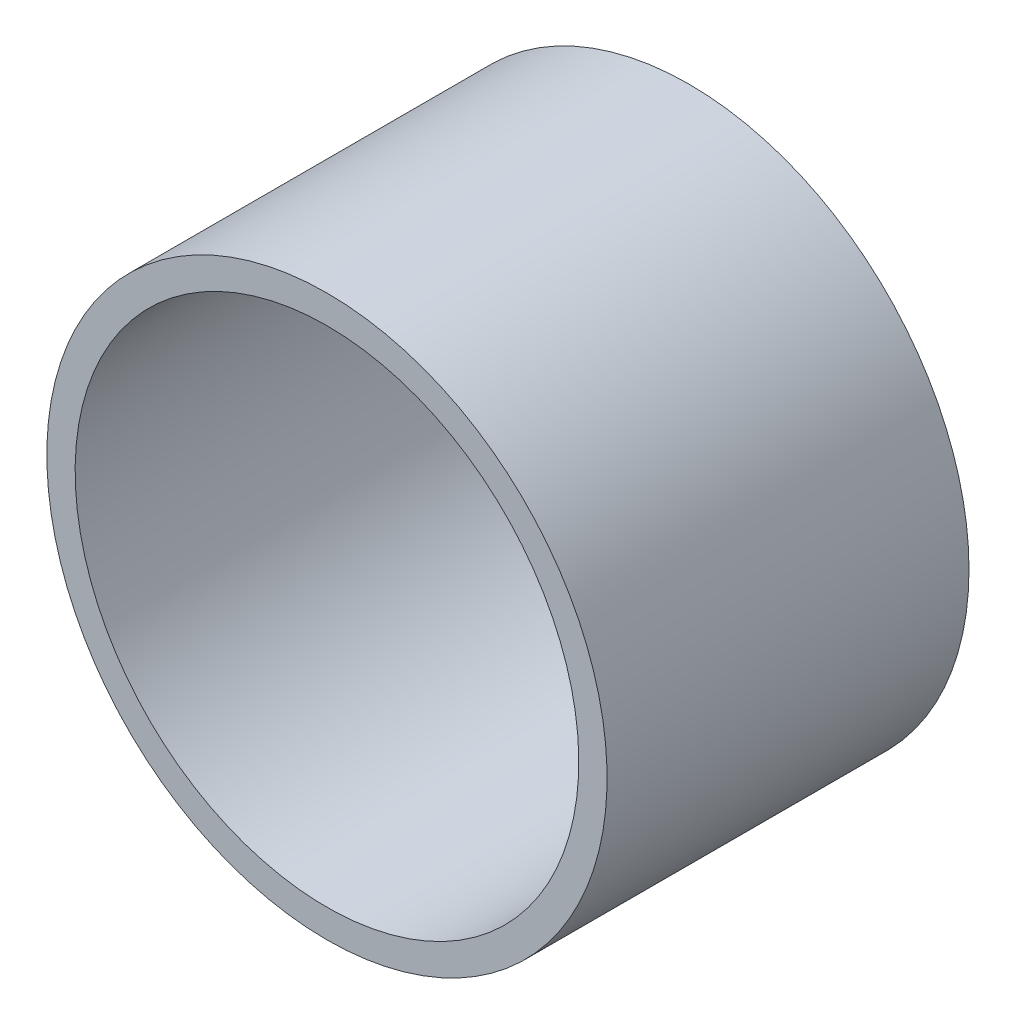
SolidWorks part; units mm, degrees
ref_plane "Front Plane" through (0, 0, 0) normal (0, 0, 1) x (1, 0, 0)
ref_plane "Top Plane" through (0, 0, 0) normal (0, 1, 0) x (1, 0, 0)
ref_plane "Right Plane" through (0, 0, 0) normal (1, 0, 0) x (0, 0, -1)
sketch "Sketch1" plane through (0, 0, 0) normal (0, 0, 1) x (1, 0, 0)
  circle A0 centre (0, 0) radius 25.146
  circle A1 centre (0, 0) radius 22.606
  dimension "D1" = 2.54
  dimension "D2" = 45.212
extrude "Boss-Extrude1" add sketch "Sketch1" along normal up to surface (32.4869 mm away)
